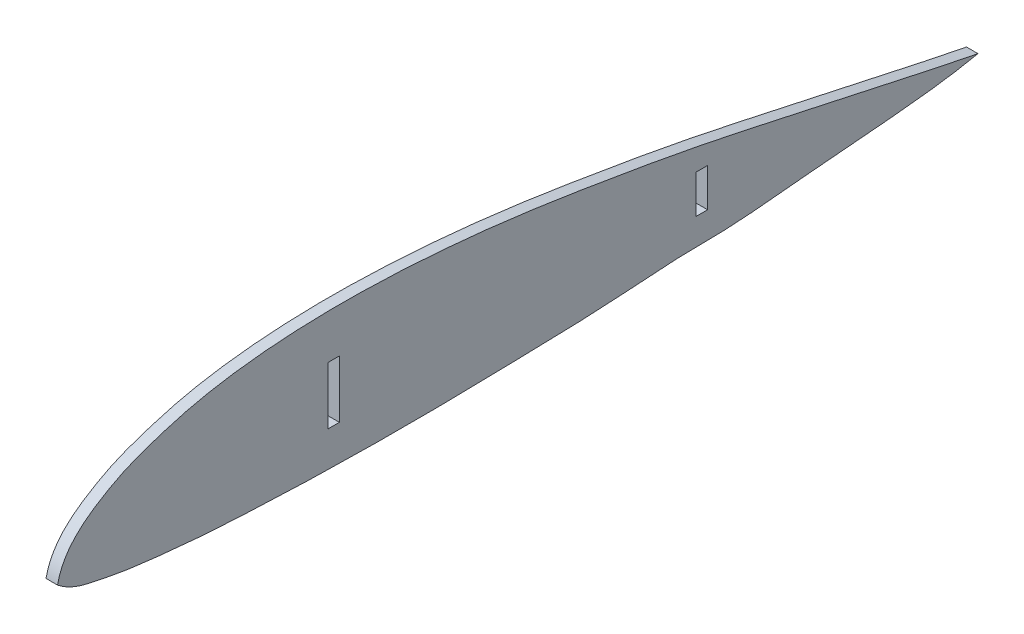
SolidWorks part; units mm, degrees
ref_plane "Спереди" through (0, 0, 0) normal (0, 0, 1) x (1, 0, 0)
ref_plane "Сверху" through (0, 0, 0) normal (0, 1, 0) x (1, 0, 0)
ref_plane "Справа" through (0, 0, 0) normal (1, 0, 0) x (0, 0, -1)
sketch "Эскиз1" plane through (0, 0, 0) normal (1, 0, 0) x (0, 0, -1)
  spline S0 degree 3 poles (-240, 0) (-238.5396, 6.886) (-231.612, 12.3378) (-222.1753, 17.4121) (-214.1119, 20.3435) (-204.1561, 23.2639) (-188.1046, 25.8933) (-168.0072, 26.9601) (-143.9456, 26.0264) (-119.9183, 23.5678) (-95.9538, 19.7588) (-71.9127, 15.562) (-48.006, 10.2206) (-23.9898, 5.1714) (-8.0375, 1.5236) (0, 0) knots 0 0 0 0 0.075346 0.102328 0.12789 0.177564 0.226025 0.321727 0.4173 0.513305 0.60992 0.706974 0.804635 0.902346 1 1 1 1
  spline S1 degree 3 poles (-240, 0) (-236.5239, -2.8866) (-230.2208, -4.0678) (-222.0286, -5.6488) (-214.0096, -6.6085) (-204.0195, -7.6506) (-188.0105, -8.621) (-168.0084, -9.355) (-143.9974, -9.5447) (-119.9964, -9.0006) (-95.9841, -8.4523) (-79.4445, -6.8615) (-63.4129, -6.9414) (-47.4215, -5.1493) (-23.952, -3.3462) (-7.916, -1.6722) (0, 0) knots 0 0 0 0 0.053475 0.078709 0.103753 0.153673 0.203448 0.302856 0.402199 0.501554 0.600955 0.70043 0.70748 0.799996 0.899716 1 1 1 1
  point P0 (-240, 0)
  point P1 (-234, 9.888)
  point P2 (-228, 14.16)
  point P3 (-222, 17.316)
  point P4 (-216, 19.608)
  point P5 (-204, 23.04)
  point P6 (-192, 25.104)
  point P7 (-168, 26.592)
  point P8 (-144, 25.776)
  point P9 (-120, 23.352)
  point P10 (-96, 19.704)
  point P11 (-72, 15.384)
  point P12 (-48, 10.272)
  point P13 (-24, 5.1)
  point P14 (-12, 2.46)
  point P15 (0, 0)
  point P16 (-234, -3.12)
  point P17 (-228, -4.5)
  point P18 (-222, -5.58)
  point P19 (-216, -6.36)
  point P20 (-204, -7.5648)
  point P21 (-192, -8.3472)
  point P22 (-168, -9.24)
  point P23 (-144, -9.4224)
  point P24 (-120, -9)
  point P25 (-96, -8.16)
  point P26 (-72, -6.9024)
  point P27 (-48, -5.34)
  point P28 (-24, -3.24)
  point P29 (-12, -1.98)
extrude "Бобышка-Вытянуть1" add sketch "Эскиз1" along normal blind 3
sketch "Эскиз2" plane through (0, 0, 0) normal (-1, 0, 0) x (0, 0, 1)
  line L13 (169.5, 0) -> (169.5, 15)
  line L14 (169.5, 15) -> (166.5, 15)
  line L15 (166.5, 0) -> (169.5, 0)
  line L16 (166.5, 15) -> (166.5, 0)
  line L17 (70.5, 0) -> (70.5, 10)
  line L18 (70.5, 0) -> (73.5, 0)
  line L19 (70.5, 10) -> (73.5, 10)
  line L20 (73.5, 10) -> (73.5, 0)
extrude "Вырез-Вытянуть1" cut sketch "Эскиз2" against normal blind 3
